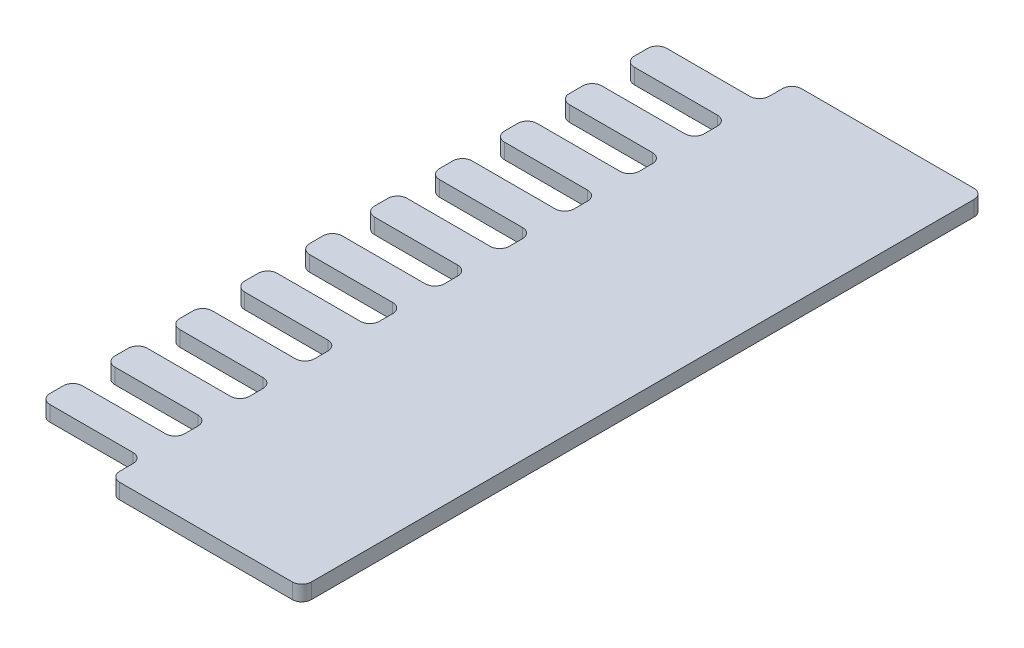
SolidWorks part; units mm, degrees
ref_plane "Front Plane" through (0, 0, 0) normal (0, 0, 1) x (1, 0, 0)
ref_plane "Top Plane" through (0, 0, 0) normal (0, 1, 0) x (1, 0, 0)
ref_plane "Right Plane" through (0, 0, 0) normal (1, 0, 0) x (0, 0, -1)
sketch "Sketch1" plane through (0, 0, 0) normal (0, 1, 0) x (1, 0, 0)
  line L0 (-0.75, 2.54) -> (-7.25, 2.54)
  line L2 (0, 1.79) -> (0, 0.75)
  line L5 (-8, 3.81) -> (5.7163, 3.81) construction
  line L7 (-8, 3.29) -> (-8, 4.33)
  line L8 (-7.25, 5.08) -> (-0.75, 5.08)
  line L12 (0, 6.87) -> (0, 5.83)
  line L17 (-0.75, 7.62) -> (-7.25, 7.62)
  line L22 (-8, 8.37) -> (-8, 9.41)
  line L27 (-7.25, 10.16) -> (-0.75, 10.16)
  line L32 (0, 11.95) -> (0, 10.91)
  line L37 (-0.75, 12.7) -> (-7.25, 12.7)
  line L42 (-8, 13.45) -> (-8, 14.49)
  line L47 (-7.25, 15.24) -> (-0.75, 15.24)
  line L52 (0, 17.03) -> (0, 15.99)
  line L53 (0, 51.55) -> (0, 52.59)
  line L54 (0.75, 53.34) -> (14.25, 53.34)
  line L55 (15, 52.59) -> (15, 0.75)
  line L56 (14.25, 0) -> (0.75, 0)
  line L57 (-0.75, 17.78) -> (-7.25, 17.78)
  line L58 (-8, 18.53) -> (-8, 19.57)
  line L59 (-7.25, 20.32) -> (-0.75, 20.32)
  line L60 (0, 22.11) -> (0, 21.07)
  line L61 (-0.75, 22.86) -> (-7.25, 22.86)
  line L62 (-8, 23.61) -> (-8, 24.65)
  line L63 (-7.25, 25.4) -> (-0.75, 25.4)
  line L64 (0, 27.19) -> (0, 26.15)
  line L65 (-0.75, 27.94) -> (-7.25, 27.94)
  line L66 (-8, 28.69) -> (-8, 29.73)
  line L67 (-7.25, 30.48) -> (-0.75, 30.48)
  line L68 (0, 32.27) -> (0, 31.23)
  line L69 (-0.75, 33.02) -> (-7.25, 33.02)
  line L70 (-8, 33.77) -> (-8, 34.81)
  line L71 (-7.25, 35.56) -> (-0.75, 35.56)
  line L72 (0, 37.35) -> (0, 36.31)
  line L73 (-0.75, 38.1) -> (-7.25, 38.1)
  line L74 (-8, 38.85) -> (-8, 39.89)
  line L75 (-7.25, 40.64) -> (-0.75, 40.64)
  line L76 (0, 42.43) -> (0, 41.39)
  line L77 (-0.75, 43.18) -> (-7.25, 43.18)
  line L78 (-8, 43.93) -> (-8, 44.97)
  line L79 (-7.25, 45.72) -> (-0.75, 45.72)
  line L80 (0, 47.51) -> (0, 46.47)
  line L81 (-0.75, 48.26) -> (-7.25, 48.26)
  line L82 (-8, 49.01) -> (-8, 50.05)
  line L83 (-7.25, 50.8) -> (-0.75, 50.8)
  arc A0 (-0.75, 5.08) -> (0, 5.83) centre (-0.75, 5.83) ccw
  arc A1 (-8, 4.33) -> (-7.25, 5.08) centre (-7.25, 4.33) cw
  arc A2 (-7.25, 2.54) -> (-8, 3.29) centre (-7.25, 3.29) cw
  arc A3 (0, 0.75) -> (0.75, 0) centre (0.75, 0.75) ccw
  arc A4 (-0.75, 2.54) -> (0, 1.79) centre (-0.75, 1.79) cw
  arc A5 (15, 0.75) -> (14.25, 0) centre (14.25, 0.75) cw
  arc A6 (-0.75, 7.62) -> (0, 6.87) centre (-0.75, 6.87) cw
  arc A7 (-7.25, 7.62) -> (-8, 8.37) centre (-7.25, 8.37) cw
  arc A8 (-8, 9.41) -> (-7.25, 10.16) centre (-7.25, 9.41) cw
  arc A9 (-0.75, 10.16) -> (0, 10.91) centre (-0.75, 10.91) ccw
  arc A10 (-0.75, 12.7) -> (0, 11.95) centre (-0.75, 11.95) cw
  arc A11 (-7.25, 12.7) -> (-8, 13.45) centre (-7.25, 13.45) cw
  arc A12 (-8, 14.49) -> (-7.25, 15.24) centre (-7.25, 14.49) cw
  arc A13 (-0.75, 15.24) -> (0, 15.99) centre (-0.75, 15.99) ccw
  arc A14 (-0.75, 17.78) -> (0, 17.03) centre (-0.75, 17.03) cw
  arc A15 (-7.25, 17.78) -> (-8, 18.53) centre (-7.25, 18.53) cw
  arc A16 (-8, 19.57) -> (-7.25, 20.32) centre (-7.25, 19.57) cw
  arc A17 (-0.75, 20.32) -> (0, 21.07) centre (-0.75, 21.07) ccw
  arc A18 (-0.75, 22.86) -> (0, 22.11) centre (-0.75, 22.11) cw
  arc A19 (-7.25, 22.86) -> (-8, 23.61) centre (-7.25, 23.61) cw
  arc A20 (-8, 24.65) -> (-7.25, 25.4) centre (-7.25, 24.65) cw
  arc A21 (-0.75, 25.4) -> (0, 26.15) centre (-0.75, 26.15) ccw
  arc A22 (-0.75, 27.94) -> (0, 27.19) centre (-0.75, 27.19) cw
  arc A23 (-7.25, 27.94) -> (-8, 28.69) centre (-7.25, 28.69) cw
  arc A24 (-8, 29.73) -> (-7.25, 30.48) centre (-7.25, 29.73) cw
  arc A25 (-0.75, 30.48) -> (0, 31.23) centre (-0.75, 31.23) ccw
  arc A26 (-0.75, 33.02) -> (0, 32.27) centre (-0.75, 32.27) cw
  arc A27 (-7.25, 33.02) -> (-8, 33.77) centre (-7.25, 33.77) cw
  arc A28 (-8, 34.81) -> (-7.25, 35.56) centre (-7.25, 34.81) cw
  arc A29 (-0.75, 35.56) -> (0, 36.31) centre (-0.75, 36.31) ccw
  arc A30 (-0.75, 38.1) -> (0, 37.35) centre (-0.75, 37.35) cw
  arc A31 (-7.25, 38.1) -> (-8, 38.85) centre (-7.25, 38.85) cw
  arc A32 (-8, 39.89) -> (-7.25, 40.64) centre (-7.25, 39.89) cw
  arc A33 (-0.75, 40.64) -> (0, 41.39) centre (-0.75, 41.39) ccw
  arc A34 (-0.75, 43.18) -> (0, 42.43) centre (-0.75, 42.43) cw
  arc A35 (-7.25, 43.18) -> (-8, 43.93) centre (-7.25, 43.93) cw
  arc A36 (-8, 44.97) -> (-7.25, 45.72) centre (-7.25, 44.97) cw
  arc A37 (-0.75, 45.72) -> (0, 46.47) centre (-0.75, 46.47) ccw
  arc A38 (-0.75, 48.26) -> (0, 47.51) centre (-0.75, 47.51) cw
  arc A39 (-7.25, 48.26) -> (-8, 49.01) centre (-7.25, 49.01) cw
  arc A40 (-8, 50.05) -> (-7.25, 50.8) centre (-7.25, 50.05) cw
  arc A41 (-0.75, 50.8) -> (0, 51.55) centre (-0.75, 51.55) ccw
  arc A42 (0, 52.59) -> (0.75, 53.34) centre (0.75, 52.59) cw
  arc A43 (14.25, 53.34) -> (15, 52.59) centre (14.25, 52.59) cw
  point P0 (0, 0)
  point P4 (0, 5.7803)
  point P11 (0, 5.8256)
  point P20 (0, 0)
  point P27 (0, 5.08)
  point P48 (-8, 5.08)
  point P69 (-8, 2.54)
  point P78 (0, 0)
  point P81 (0, 2.54)
  point P84 (15, 0)
  dimension "D6" = 0.75
  dimension "D7" = 0.75
  dimension "D8" = 0.75
  dimension "D9" = 0.75
  dimension "D1" = 2.54
  dimension "D2" = 8
  dimension "D3" = 10
  dimension "D4" = 2.54
  dimension "D5" = 15
extrude "Boss-Extrude1" add sketch "Sketch1" along normal blind 1.2
